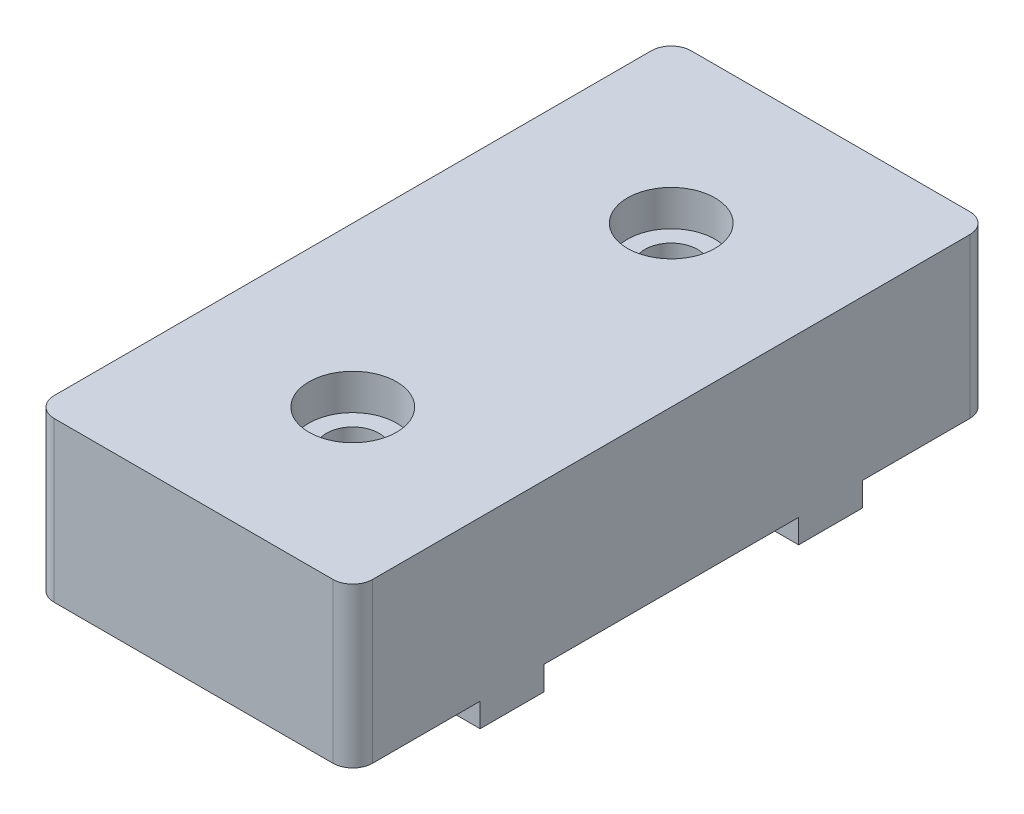
SolidWorks part; units mm, degrees
material "5052-H32"
ref_plane "Front Plane" through (0, 0, 0) normal (0, 0, 1) x (1, 0, 0)
ref_plane "Top Plane" through (0, 0, 0) normal (0, 1, 0) x (1, 0, 0)
ref_plane "Right Plane" through (0, 0, 0) normal (1, 0, 0) x (0, 0, -1)
sketch "Sketch1" plane through (0, 0, 0) normal (0, 1, 0) x (1, 0, 0)
  line L1 (20, -40) -> (-20, -40)
  line L2 (20, -40) -> (20, 40)
  line L3 (20, 40) -> (-20, 40)
  line L4 (-20, -40) -> (-20, 40)
  line L5 (20, -40) -> (-20, 40) construction
  line L6 (20, 40) -> (-20, -40) construction
  point P0 (0, 0)
  dimension "D1" = 40
  dimension "D2" = 80
extrude "Boss-Extrude1" add sketch "Sketch1" along normal blind 20
sketch "Sketch2" plane through (0, 0, 0) normal (0, 1, 0) x (1, 0, 0)
  line L0 (-20, 40) -> (-20, -40) construction
  line L1 (-20, -24) -> (20, -24)
  line L2 (-20, -24) -> (-20, -16)
  line L3 (-20, -16) -> (20, -16)
  line L4 (20, -24) -> (20, -16)
  line L5 (20, -40) -> (20, 40) construction
  line L7 (20, 24) -> (-20, 24)
  line L8 (20, 24) -> (20, 16)
  line L9 (20, 16) -> (-20, 16)
  line L10 (-20, 24) -> (-20, 16)
  point P12 (-20, -20)
  point P14 (-20, 20)
  dimension "D1" = 8
  dimension "D2" = 20
  dimension "D3" = 40
extrude "Boss-Extrude2" add sketch "Sketch2" against normal blind 3
hole_wizard "CBORE for M6 Hex Socket Thin Head Cap Screw1" positions "Sketch3" profile "Sketch4" counterbore size "M6" standard "DIN"
sketch "Sketch3" plane through (0, 20, 0) normal (0, 1, 0) x (1, 0, 0)
  point P0 (0, -20)
  point P2 (0, 20)
  dimension "D1" = 20
  dimension "D2" = 40
sketch "Sketch4" plane through (0, 20, 20) normal (1, 0, 0) x (0, 0, 1)
  line L0 (0, 0) -> (0, 24.5)
  line L1 (0, 24.5) -> (3.3, 24.5)
  line L2 (3.3, 24.5) -> (3.3, 4.5)
  line L3 (3.3, 4.5) -> (5.5, 4.5)
  line L4 (5.5, 4.5) -> (5.5, 0)
  line L5 (5.5, 0) -> (0, 0)
  line L10 (0, 24.5) -> (-3.3, 24.5) construction
  line L11 (0, -6.35) -> (0, 107.95) construction
  dimension "Hole Dia." = 6.6
  dimension "Hole Depth" = 24.5
  dimension "C'Bore Dia." = 11
  dimension "C'Bore Depth" = 4.5
  dimension "Drill Angle" = 180
hole_wizard "M8 Tapped Hole1" positions "Sketch5" profile "Sketch7" tap size "M8" standard "DIN"
sketch "Sketch5" plane through (-20, 0, 0) normal (-1, 0, 0) x (0, 0, 1)
  line L0 (-40, 20) -> (-40, 0) construction
  point P0 (0, 10)
  point P8 (-40, 10)
cosmetic thread "Hole Thread2" parameters "D1"=30, "D2"=8
sketch "Sketch7" plane through (-20, 10, 0) normal (0, 1, 0) x (0, 0, 1)
  line L0 (0, 0) -> (0, 33.75)
  line L1 (0, 33.75) -> (3.4, 33.75)
  line L2 (3.4, 33.75) -> (3.4, 0)
  line L5 (3.4, 0) -> (0, 0)
  line L10 (0, 33.75) -> (-3.4, 33.75) construction
  line L11 (0, -6.35) -> (0, 107.95) construction
  dimension "Tap Drill Dia." = 6.8
  dimension "Tap Drill Depth" = 33.75
  dimension "Drill Angle" = 180
fillet "Fillet1" radius 2.5 4 edges at (20, 10, -40) (-20, 10, -40) (-20, 10, 40) (20, 10, 40)
